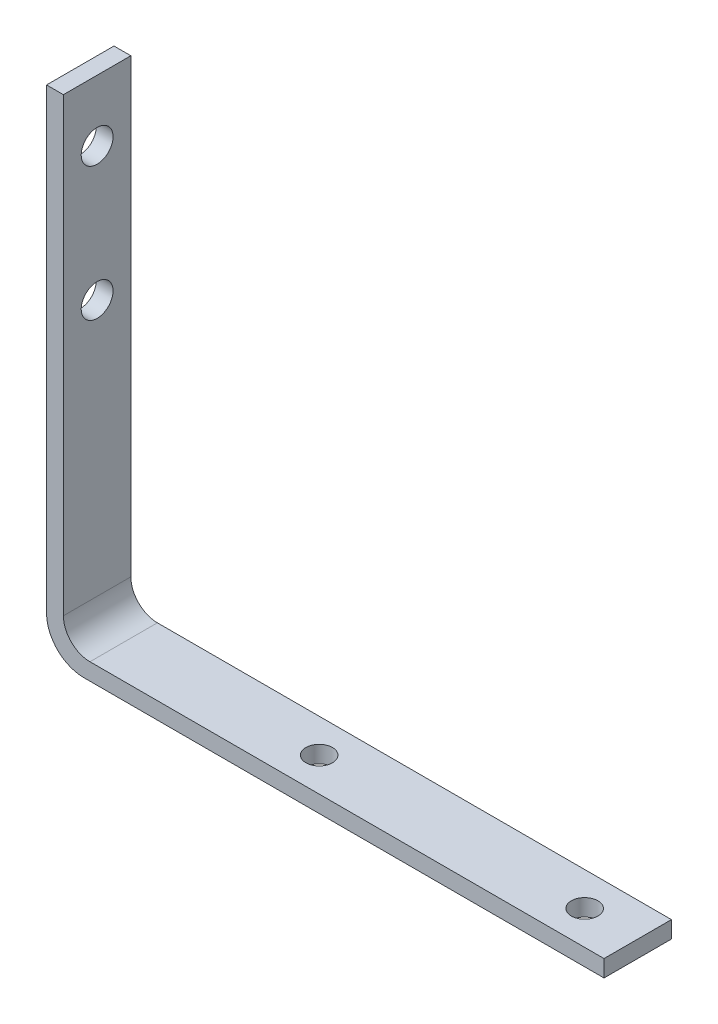
SolidWorks part; units mm, degrees
ref_plane "Front Plane" through (0, 0, 0) normal (0, 0, 1) x (1, 0, 0)
ref_plane "Top Plane" through (0, 0, 0) normal (0, 1, 0) x (1, 0, 0)
ref_plane "Right Plane" through (0, 0, 0) normal (1, 0, 0) x (0, 0, -1)
sketch "Sketch1" plane through (0, 0, 0) normal (0, 1, 0) x (1, 0, 0)
  line L0 (-52.5, 0) -> (52.5, 0) construction
  line L1 (-52.5, -6.35) -> (52.5, -6.35)
  line L2 (-52.5, -6.35) -> (-52.5, 6.35)
  line L3 (-52.5, 6.35) -> (52.5, 6.35)
  line L4 (52.5, -6.35) -> (52.5, 6.35)
  line L5 (-52.5, -6.35) -> (52.5, 6.35) construction
  line L6 (-52.5, 6.35) -> (52.5, -6.35) construction
  circle A0 centre (42.5, 0) radius 2.5
  circle A1 centre (-7.5, 0) radius 2.5
  point P0 (0, 0)
  dimension "D3" = 5
  dimension "D1" = 105
  dimension "D2" = 12.7
  dimension "D4" = 10
  dimension "D5" = 50
extrude "Boss-Extrude1" add sketch "Sketch1" along normal blind 3.175
sketch "Sketch2" plane through (0, 3.175, 0) normal (0, 1, 0) x (1, 0, 0)
  line L0 (-52.5, -6.35) -> (52.5, -6.35) construction
  line L1 (-52.5, 6.35) -> (-49.325, 6.35)
  line L2 (-52.5, 6.35) -> (-52.5, -6.35)
  line L3 (-52.5, -6.35) -> (-49.325, -6.35)
  line L4 (-49.325, 6.35) -> (-49.325, -6.35)
  line L5 (-52.5, 6.35) -> (-52.5, -6.35) construction
  dimension "D1" = 3.175
extrude "Boss-Extrude2" add sketch "Sketch2" along normal blind 90
sketch "Sketch3" plane through (-52.5, 0, 0) normal (-1, 0, 0) x (0, 0, 1)
  line L0 (0, 0) -> (0, 93.175) construction
  line L1 (-6.35, 0) -> (6.35, 0) construction
  line L2 (-6.35, 93.175) -> (6.35, 93.175) construction
  line L3 (-6.35, 40) -> (6.35, 40) construction
  line L4 (-6.35, 93.175) -> (-6.35, 0) construction
  line L5 (6.35, 93.175) -> (6.35, 0) construction
  circle A0 centre (0, 56.51) radius 3
  circle A1 centre (0, 81.656) radius 3
  dimension "D1" = 6
  dimension "D5" = 6
  dimension "D2" = 40
  dimension "D3" = 16.51
  dimension "D4" = 25.146
extrude "Cut-Extrude1" cut sketch "Sketch3" against normal blind 3.175 contours A0 | A1
fillet "Fillet1" radius 5 1 edges at (-49.325, 3.175, 0)
fillet "Fillet2" radius 7 1 edges at (-52.5, 0, 0)
